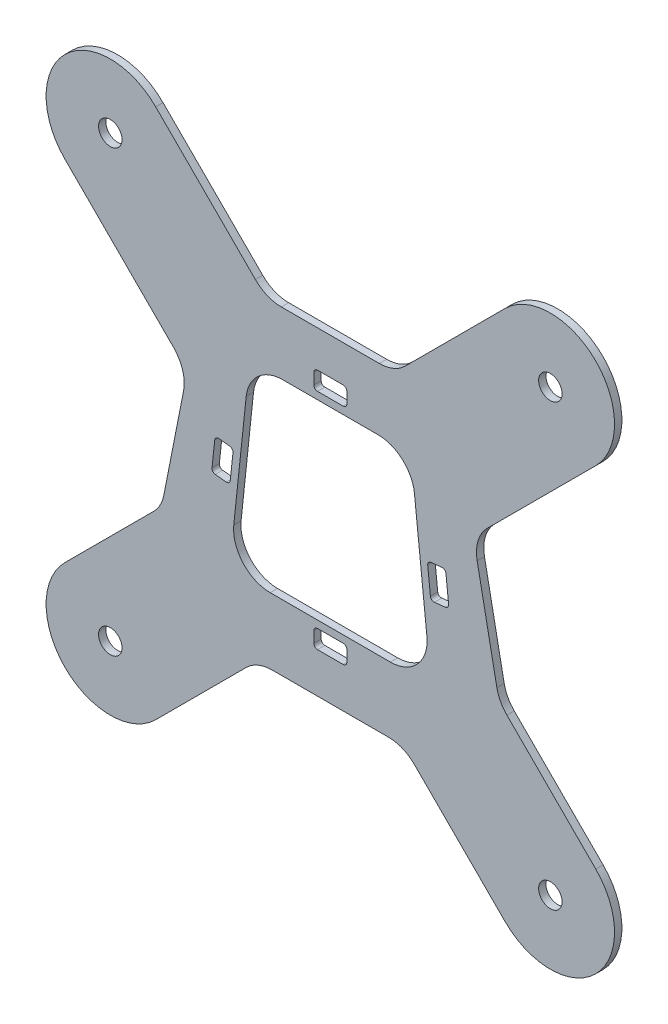
SolidWorks part; units mm, degrees
material "3.0205 (EN-AW 1200)"
ref_plane "Front" through (0, 0, 0) normal (0, 0, 1) x (1, 0, 0)
ref_plane "Top" through (0, 0, 0) normal (0, 1, 0) x (1, 0, 0)
ref_plane "Right" through (0, 0, 0) normal (1, 0, 0) x (0, 0, -1)
sketch "Skizze1" plane through (0, 0, 0) normal (0, 0, 1) x (1, 0, 0)
  line L0 (0, 71.0976) -> (0, -89.5446) construction
  line L1 (17.5, 44.5) -> (-17.5, 44.5)
  line L2 (-17.5, 44.5) -> (-47.6256, 74.6256)
  line L3 (0, 0) -> (90.1321, 0) construction
  line L4 (-72.3744, 49.8769) -> (-39, 16.5025)
  line L5 (-39, 16.5025) -> (-46, -19)
  line L6 (-46, -19) -> (-72.3744, -45.3744)
  line L7 (17.5, 44.5) -> (47.6256, 74.6256)
  line L8 (-47.6256, -70.1231) -> (-20, -42.4975)
  line L9 (-20, -42.4975) -> (20, -42.4975)
  line L10 (47.6256, -70.1231) -> (20, -42.4975)
  line L11 (46, -19) -> (72.3744, -45.3744)
  line L12 (39, 16.5025) -> (46, -19)
  line L13 (72.3744, 49.8769) -> (39, 16.5025)
  arc A0 (-47.6256, 74.6256) -> (-72.3744, 49.8769) centre (-60, 62.2513) ccw
  arc A1 (-72.3744, -45.3744) -> (-47.6256, -70.1231) centre (-60, -57.7487) ccw
  arc A2 (72.3744, -45.3744) -> (47.6256, -70.1231) centre (60, -57.7487) cw
  arc A3 (47.6256, 74.6256) -> (72.3744, 49.8769) centre (60, 62.2513) cw
  point P24 (0, -42.4975)
  point P31 (0, 44.5)
  dimension "D3" = 17.5
  dimension "D4" = 17.5
  dimension "D1" = 120
  dimension "D2" = 120
  dimension "D5" = 17.5
  dimension "D6" = 45
  dimension "D7" = 120
  dimension "D8" = 44.5
  dimension "D9" = 46
  dimension "D10" = 20
  dimension "D11" = 45
  dimension "D12" = 39
extrude "Aufsatz-Linear austragen1" add sketch "Skizze1" along normal blind 2
sketch "Skizze2" plane through (0, 0, 2) normal (0, 0, 1) x (1, 0, 0)
  line L0 (0, 0) -> (0, 72.9114) construction
  line L1 (0, 0) -> (75.4304, 0) construction
  arc A0 (-47.6256, 74.6256) -> (-72.3744, 49.8769) centre (-60, 62.2513) ccw construction
  arc A1 (-47.6256, 74.6256) -> (-72.3744, 49.8769) centre (-60, 62.2513) ccw
  arc A2 (72.3744, 49.8769) -> (47.6256, 74.6256) centre (60, 62.2513) ccw construction
  arc A7 (72.3744, 49.8769) -> (47.6256, 74.6256) centre (60, 62.2513) ccw
  arc A8 (47.6256, -70.1231) -> (72.3744, -45.3744) centre (60, -57.7487) ccw construction
  arc A9 (-72.3744, -45.3744) -> (-47.6256, -70.1231) centre (-60, -57.7487) ccw construction
  arc A10 (47.6256, -70.1231) -> (72.3744, -45.3744) centre (60, -57.7487) ccw
  arc A11 (-72.3744, -45.3744) -> (-47.6256, -70.1231) centre (-60, -57.7487) ccw
  circle A12 centre (-60, 62.2513) radius 3.2
  circle A13 centre (-60, -57.7487) radius 3.2
  circle A14 centre (60, 62.2513) radius 3.2
  circle A15 centre (60, -57.7487) radius 3.2
  dimension "D1" = 6.4
  dimension "D2" = 6.4
  dimension "D3" = 6.4
  dimension "D4" = 6.4
extrude "Schnitt-Linear austragen1" cut sketch "Skizze2" against normal up to surface (2 mm away) contours A13 | A12 | A15 | A14 up to face at (0, 1.0638, 0)
sketch "Skizze3" plane through (0, 0, 2) normal (0, 0, 1) x (1, 0, 0)
  line L0 (-47.6256, 74.6256) -> (-72.3744, 49.8769) construction
  line L1 (-72.3744, 49.8769) -> (-39, 16.5025) construction
  line L2 (0, 0) -> (0, 61.1458) construction
  line L3 (0, 0) -> (66.1963, 0) construction
  line L4 (47.6256, 74.6256) -> (72.3744, 49.8769) construction
  line L5 (72.3744, -45.3744) -> (47.6256, -70.1231) construction
  line L6 (-47.6256, -70.1231) -> (-72.3744, -45.3744) construction
  line L7 (-47.6256, -70.1231) -> (-20, -42.4975) construction
  line L8 (72.3744, -45.3744) -> (46, -19) construction
  line L9 (47.6256, 74.6256) -> (17.5, 44.5) construction
  circle A0 centre (-68.1317, 54.1195) radius 2
  circle A1 centre (51.8683, 70.383) radius 2
  circle A2 centre (68.1317, -49.617) radius 2
  circle A3 centre (-51.8683, -65.8805) radius 2
  dimension "D1" = 4
  dimension "D3" = 4
  dimension "D5" = 4
  dimension "D7" = 4
  dimension "D2" = 6
  dimension "D4" = 6
  dimension "D6" = 6
  dimension "D8" = 6
extrude "Schnitt-Linear austragen2" [suppressed] cut sketch "Skizze3" against normal up to surface (2 mm away)
sketch "Skizze4" plane through (0, 0, 2) normal (0, 0, 1) x (1, 0, 0)
  line L0 (0, 0) -> (0, 33.128) construction
  line L1 (0, 0) -> (41.765, 0) construction
  line L2 (-22, 27.5) -> (22, 27.5)
  line L3 (22, 27.5) -> (27.5, -24.5)
  line L4 (27.5, -24.5) -> (-27.5, -24.5)
  line L5 (-27.5, -24.5) -> (-22, 27.5)
  line L6 (17.5, 44.5) -> (-17.5, 44.5) construction
  dimension "D1" = 17
  dimension "D2" = 52
  dimension "D3" = 44
  dimension "D4" = 55
extrude "Schnitt-Linear austragen3" cut sketch "Skizze4" against normal up to surface (2 mm away) up to face at (-56.8, 62.2513, 0)
fillet "Verrundung1" radius 10 4 edges at (-27.5, -24.5, 1) (27.5, -24.5, 1) (22, 27.5, 1) (-22, 27.5, 1)
fillet "Verrundung2" radius 10 8 edges at (46, -19, 1) (39, 16.5025, 1) (-17.5, 44.5, 1) (17.5, 44.5, 1) (-46, -19, 1) (-39, 16.5025, 1) (-20, -42.4975, 1) (20, -42.4975, 1)
sketch "Skizze5" plane through (0, 0, 2) normal (0, 0, 1) x (1, 0, 0)
  line L1 (-3.5, 34.5) -> (3.5, 34.5)
  line L2 (-4.5, 33.5) -> (-4.5, 30.5)
  line L3 (-3.5, 29.5) -> (3.5, 29.5)
  line L4 (4.5, 33.5) -> (4.5, 30.5)
  line L13 (-30.4243, 4.8958) -> (-27.4409, 4.5802)
  line L14 (-31.5239, 4.0065) -> (-32.2602, -2.9547)
  line L15 (-31.3709, -4.0543) -> (-28.3876, -4.3699)
  line L16 (-26.5517, 3.4806) -> (-27.2879, -3.4806)
  line L17 (-22.9464, 18.5518) -> (-26.3311, -13.4482) construction
  line L18 (0, 0) -> (0, 13.3086) construction
  line L19 (0, 0) -> (16.6933, 0) construction
  line L20 (13.0019, 27.5) -> (-13.0019, 27.5) construction
  line L21 (26.5517, 3.4806) -> (27.2879, -3.4806)
  line L22 (31.3709, -4.0543) -> (28.3876, -4.3699)
  line L23 (31.5239, 4.0065) -> (32.2602, -2.9547)
  line L24 (30.4243, 4.8958) -> (27.4409, 4.5802)
  line L25 (4.5, -30.5) -> (4.5, -27.5)
  line L26 (-3.5, -26.5) -> (3.5, -26.5)
  line L27 (-4.5, -30.5) -> (-4.5, -27.5)
  line L28 (-3.5, -31.5) -> (3.5, -31.5)
  line L30 (-16.3865, -24.5) -> (16.3865, -24.5) construction
  arc A0 (-3.5, -31.5) -> (-4.5, -30.5) centre (-3.5, -30.5) cw
  arc A1 (4.5, -30.5) -> (3.5, -31.5) centre (3.5, -30.5) cw
  arc A2 (3.5, -26.5) -> (4.5, -27.5) centre (3.5, -27.5) cw
  arc A3 (-3.5, -26.5) -> (-4.5, -27.5) centre (-3.5, -27.5) ccw
  arc A4 (4.5, 33.5) -> (3.5, 34.5) centre (3.5, 33.5) ccw
  arc A5 (4.5, 30.5) -> (3.5, 29.5) centre (3.5, 30.5) cw
  arc A6 (-3.5, 29.5) -> (-4.5, 30.5) centre (-3.5, 30.5) cw
  arc A7 (-4.5, 33.5) -> (-3.5, 34.5) centre (-3.5, 33.5) cw
  arc A8 (31.5239, 4.0065) -> (30.4243, 4.8958) centre (30.5295, 3.9013) ccw
  arc A9 (32.2602, -2.9547) -> (31.3709, -4.0543) centre (31.2658, -3.0599) cw
  arc A10 (28.3876, -4.3699) -> (27.2879, -3.4806) centre (28.2824, -3.3754) cw
  arc A11 (26.5517, 3.4806) -> (27.4409, 4.5802) centre (27.5461, 3.5858) cw
  arc A12 (-26.5517, 3.4806) -> (-27.4409, 4.5802) centre (-27.5461, 3.5858) ccw
  arc A13 (-28.3876, -4.3699) -> (-27.2879, -3.4806) centre (-28.2824, -3.3754) ccw
  arc A14 (-31.3709, -4.0543) -> (-32.2602, -2.9547) centre (-31.2658, -3.0599) cw
  arc A15 (-31.5239, 4.0065) -> (-30.4243, 4.8958) centre (-30.5295, 3.9013) cw
  point P4 (-26.9198, 0)
  point P6 (0, 0)
  point P8 (0, 0)
  point P23 (26.9198, 0)
  point P30 (0, -24.5)
  point P41 (4.5, 34.5)
  point P46 (-4.5, 29.5)
  point P49 (-4.5, 34.5)
  point P52 (31.4188, 5.001)
  point P55 (32.3654, -3.9491)
  point P58 (27.3931, -4.475)
  point P61 (26.4465, 4.475)
  point P64 (-26.4465, 4.475)
  point P67 (-27.3931, -4.475)
  point P70 (-32.3654, -3.9491)
  point P73 (-31.4188, 5.001)
  dimension "D6" = 1
  dimension "D1" = 5
  dimension "D2" = 9
  dimension "D3" = 2
  dimension "D4" = 2
  dimension "D5" = 2
extrude "Schnitt-Linear austragen4" cut sketch "Skizze5" against normal through all and the other way through all
